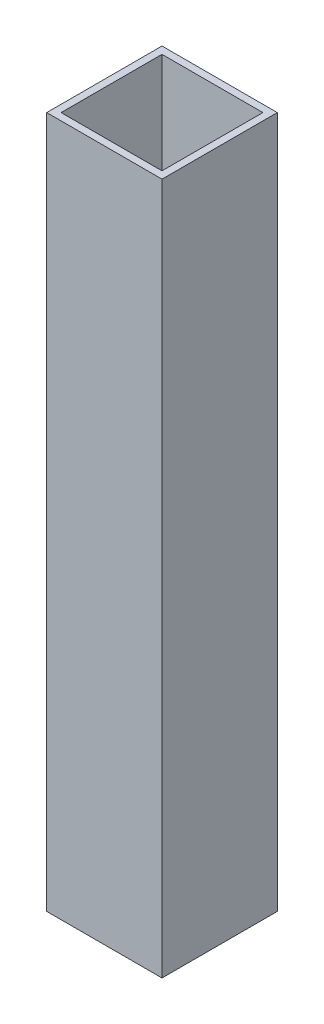
SolidWorks part; units mm, degrees
material "6061 Alloy"
ref_plane "Front Plane" through (0, 0, 0) normal (0, 0, 1) x (1, 0, 0)
ref_plane "Top Plane" through (0, 0, 0) normal (0, 1, 0) x (1, 0, 0)
ref_plane "Right Plane" through (0, 0, 0) normal (1, 0, 0) x (0, 0, -1)
sketch "Sketch1" plane through (0, 0, 0) normal (0, 1, 0) x (1, 0, 0)
  line L1 (-12.7, -12.7) -> (12.7, -12.7)
  line L2 (-12.7, -12.7) -> (-12.7, 12.7)
  line L3 (-12.7, 12.7) -> (12.7, 12.7)
  line L4 (12.7, -12.7) -> (12.7, 12.7)
  line L7 (-11.1125, -11.1125) -> (11.1125, -11.1125)
  line L8 (-11.1125, -11.1125) -> (-11.1125, 11.1125)
  line L9 (-11.1125, 11.1125) -> (11.1125, 11.1125)
  line L10 (11.1125, -11.1125) -> (11.1125, 11.1125)
  point P6 (0, 0)
  dimension "D1" = 25.4
  dimension "D2" = 25.4
  dimension "D3" = 1.5875
  dimension "D4" = 1.5875
  dimension "D5" = 1.5875
extrude "Boss-Extrude1" add sketch "Sketch1" along normal blind 152.4
